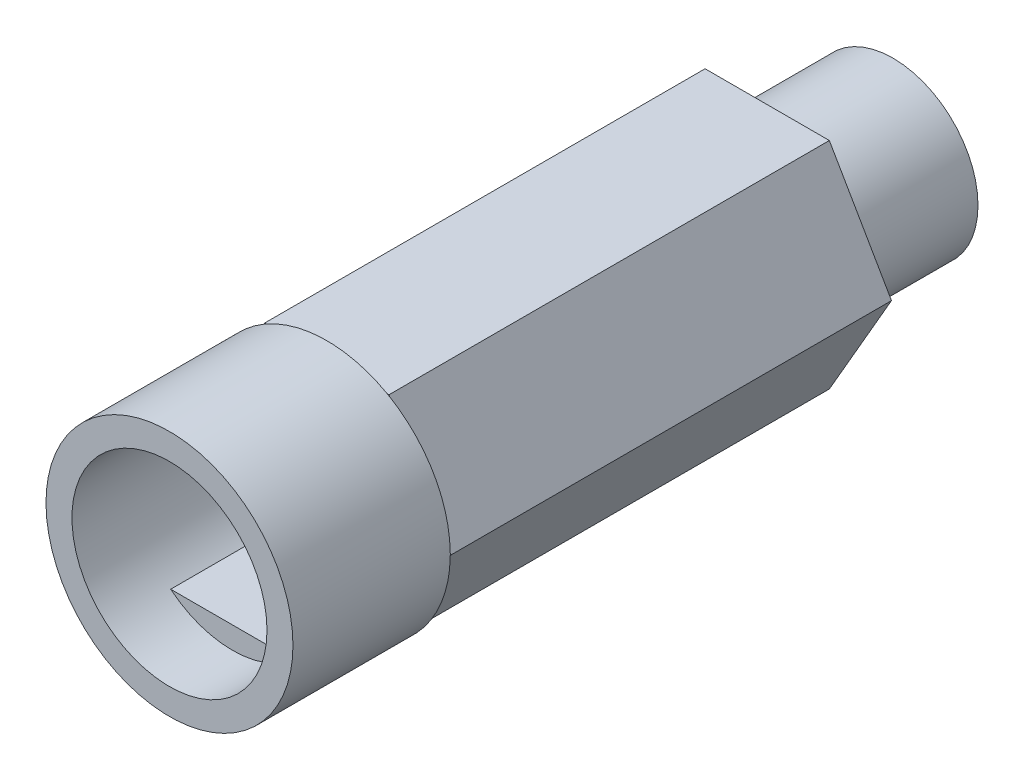
SolidWorks part; units mm, degrees
ref_plane "Front Plane" through (0, 0, 0) normal (0, 0, 1) x (1, 0, 0)
ref_plane "Top Plane" through (0, 0, 0) normal (0, 1, 0) x (1, 0, 0)
ref_plane "Right Plane" through (0, 0, 0) normal (1, 0, 0) x (0, 0, -1)
sketch "Sketch1" plane through (0, 0, 0) normal (0, 0, 1) x (1, 0, 0)
  line L1 (3.95, 0) -> (1.975, 3.4208)
  line L2 (1.975, 3.4208) -> (-1.975, 3.4208)
  line L3 (-1.975, 3.4208) -> (-3.95, 0)
  line L4 (-3.95, 0) -> (-1.975, -3.4208)
  line L5 (-1.975, -3.4208) -> (1.975, -3.4208)
  line L6 (1.975, -3.4208) -> (3.95, 0)
  circle A0 centre (0, 0) radius 3.95 construction
  circle A1 centre (0, 0) radius 3.4208 construction
  dimension "D1" = 7.9
extrude "Boss-Extrude1" add sketch "Sketch1" along normal blind 14
sketch "Sketch2" plane through (0, 0, 14) normal (0, 0, 1) x (1, 0, 0)
  circle A0 centre (0, 0) radius 3.925
  dimension "7.85" = 7.85
extrude "Boss-Extrude2" add sketch "Sketch2" along normal blind 5
sketch "Sketch3" plane through (0, 0, 0) normal (0, 0, -1) x (-1, 0, 0)
  circle A0 centre (0, 0) radius 2.7
  dimension "D1" = 5.4
extrude "Boss-Extrude3" add sketch "Sketch3" along normal blind 4
sketch "Sketch4" plane through (0, 0, 19) normal (0, 0, 1) x (1, 0, 0)
  line L0 (-1.9621, -2.4) -> (1.9621, -2.4)
  circle A0 centre (0, 0) radius 3.1
  dimension "D1" = 6.2
  dimension "5.5" = 5.5
extrude "Cut-Extrude1" cut sketch "Sketch4" against normal blind 16 contours L0 A0
sketch "Sketch5" plane through (0, 0, 19) normal (0, 0, 1) x (1, 0, 0)
  arc A0 (1.9621, -2.4) -> (-1.9621, -2.4) centre (0, 0) ccw construction
  arc A1 (1.9621, -2.4) -> (-1.9621, -2.4) centre (0, 0) ccw construction
  circle A2 centre (0, 0) radius 3.1
extrude "Cut-Extrude2" cut sketch "Sketch5" against normal blind 2
